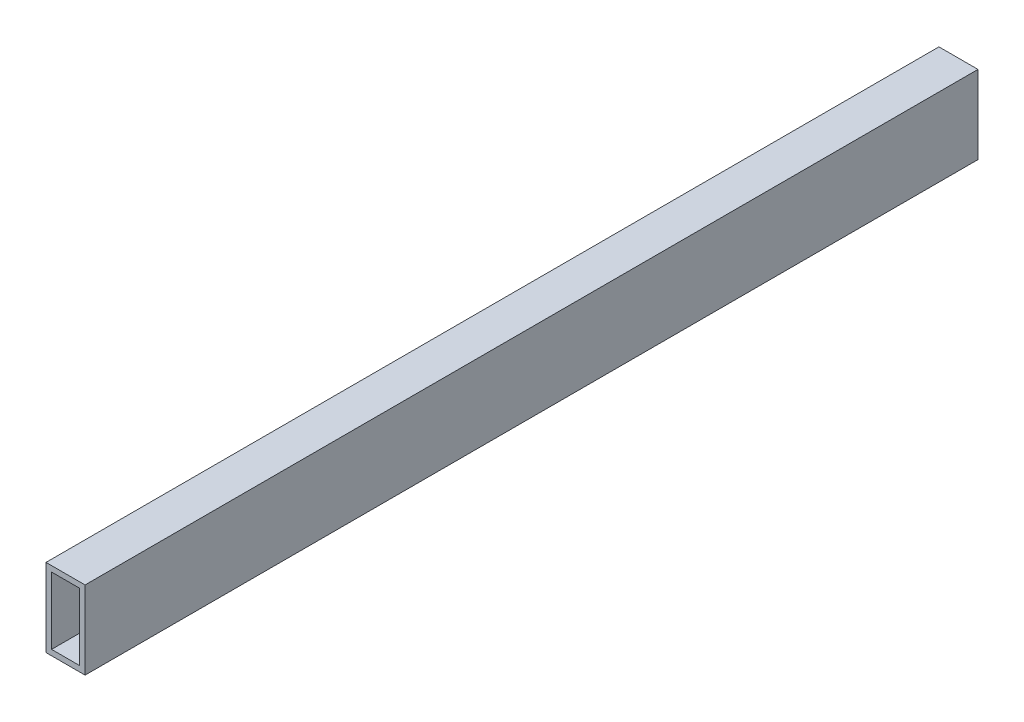
SolidWorks part; units mm, degrees
ref_plane "Front Plane" through (0, 0, 0) normal (0, 0, 1) x (1, 0, 0)
ref_plane "Top Plane" through (0, 0, 0) normal (0, 1, 0) x (1, 0, 0)
ref_plane "Right Plane" through (0, 0, 0) normal (1, 0, 0) x (0, 0, -1)
sketch "Sketch1" plane through (0, 0, 0) normal (0, 0, 1) x (1, 0, 0)
  line L0 (0, 0) -> (-7, 0)
  line L1 (0, 0) -> (0, 14)
  line L2 (0, 14) -> (-7, 14)
  line L3 (-7, 14) -> (-7, 0)
  line L4 (-3.5, 14) -> (-3.5, 0) construction
  line L6 (-6, 1) -> (-1, 1)
  line L7 (-6, 1) -> (-6, 13)
  line L8 (-6, 13) -> (-1, 13)
  line L9 (-1, 1) -> (-1, 13)
  line L10 (-6, 1) -> (-1, 13) construction
  line L11 (-6, 13) -> (-1, 1) construction
  point P7 (-3.5, 7)
  point P12 (0, 0)
extrude "Boss-Extrude1" add sketch "Sketch1" along normal blind 160
